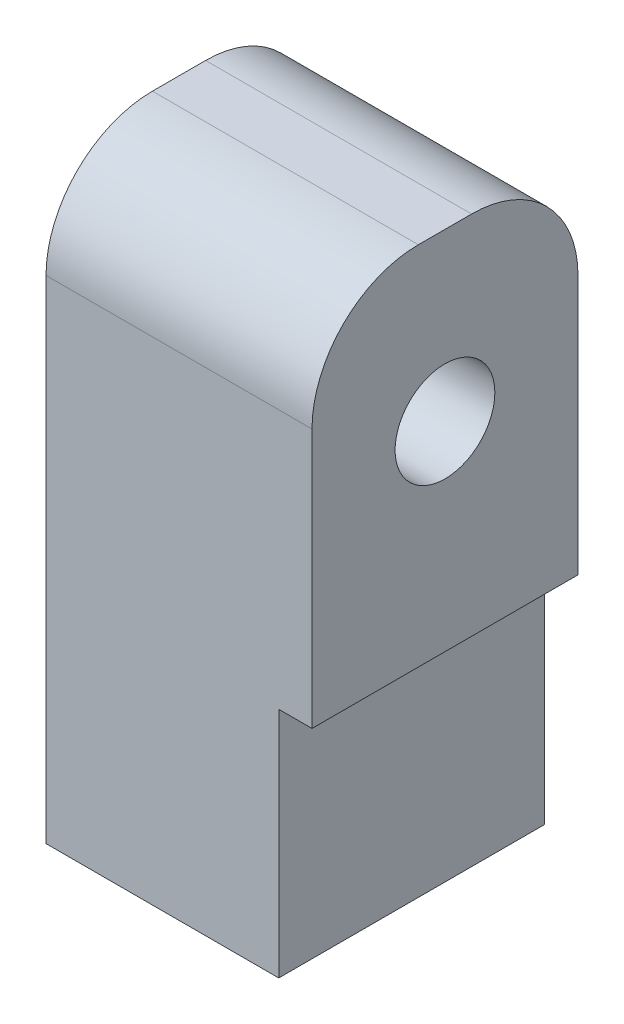
SolidWorks part; units mm, degrees
ref_plane "Front Plane" through (0, 0, 0) normal (0, 0, 1) x (1, 0, 0)
ref_plane "Top Plane" through (0, 0, 0) normal (0, 1, 0) x (1, 0, 0)
ref_plane "Right Plane" through (0, 0, 0) normal (1, 0, 0) x (0, 0, -1)
sketch "Sketch1" plane through (0, 0, 0) normal (0, 1, 0) x (1, 0, 0)
  line L1 (-0.4375, 0.5) -> (0.4375, 0.5)
  line L2 (-0.4375, 0.5) -> (-0.4375, -0.5)
  line L3 (-0.4375, -0.5) -> (0.4375, -0.5)
  line L4 (0.4375, 0.5) -> (0.4375, -0.5)
  line L5 (-0.4375, 0.5) -> (0.4375, -0.5) construction
  line L6 (-0.4375, -0.5) -> (0.4375, 0.5) construction
  point P0 (0, 0)
  dimension "D1" = 0.875
  dimension "D2" = 1
extrude "Boss-Extrude1" add sketch "Sketch1" along normal blind 0.875
sketch "Sketch2" plane through (0, 0.875, 0) normal (0, 1, 0) x (1, 0, 0)
  line L5 (-0.5, 0.5) -> (0.5, -0.5) construction
  line L6 (-0.5, -0.5) -> (0.5, 0.5) construction
  line L7 (-0.4375, -0.5) -> (0.5625, -0.5)
  line L8 (0.5625, -0.5) -> (0.5625, 0.5)
  line L9 (0.5625, 0.5) -> (-0.4375, 0.5)
  line L10 (-0.4375, 0.5) -> (-0.4375, -0.5)
  point P0 (0, 0)
  dimension "D1" = 1
extrude "Boss-Extrude2" add sketch "Sketch2" along normal blind 1.375
sketch "Sketch3" plane through (0.5625, 0, 0) normal (1, 0, 0) x (0, 0, -1)
  line L0 (-0.5, 2.25) -> (0.5, 2.25) construction
  line L5 (0.5, 2.25) -> (0.5, 0.875) construction
  circle A0 centre (0, 1.625) radius 0.1875
  point P6 (0.5, 1.6604)
  point P7 (-1.3052, 1.1648)
  dimension "D1" = 0.375
  dimension "D2" = 0.625
  dimension "D3" = 0.5
extrude "Cut-Extrude1" cut sketch "Sketch3" against normal blind 1
sketch "Sketch4" plane through (-0.4375, 0, 0) normal (-1, 0, 0) x (0, 0, 1)
  circle A0 centre (0, 1.625) radius 0.2375
  dimension "D1" = 0.475
extrude "Cut-Extrude2" cut sketch "Sketch4" against normal blind 0.125
sketch "Sketch5" plane through (0, 0, 0) normal (0, -1, 0) x (1, 0, 0)
  line L0 (-0.4375, -0.5) -> (-0.4375, 0.5) construction
  line L1 (-0.4375, 0.5) -> (0.4375, 0.5) construction
  circle A1 centre (0.0625, 0) radius 0.25
  point P7 (-0.4045, 0.0222)
  dimension "D1" = 0.5
  dimension "D3" = 0.5
  dimension "D2" = 0.5
extrude "Cut-Extrude3" cut sketch "Sketch5" against normal blind 1.188
fillet "Fillet1" radius 0.4 2 edges at (0.0625, 2.25, -0.5) (0.0625, 2.25, 0.5)
